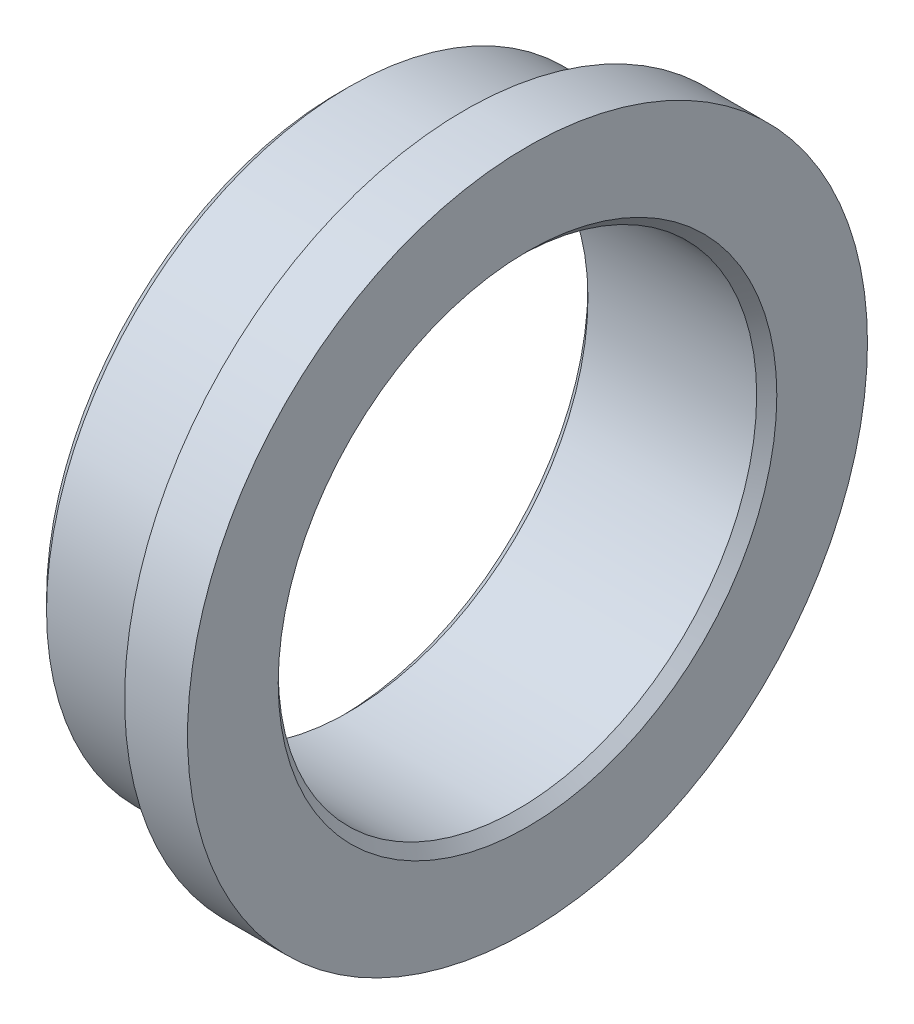
SolidWorks part; units mm, degrees
material "2.1030 (CuSn8P)"
ref_plane "Ebene vorne" through (0, 0, 0) normal (0, 0, 1) x (1, 0, 0)
ref_plane "Ebene oben" through (0, 0, 0) normal (0, 1, 0) x (1, 0, 0)
ref_plane "Ebene rechts" through (0, 0, 0) normal (1, 0, 0) x (0, 0, -1)
ref_axis "A_Drehachse" through (6.5, 0, 0) along (-1, 0, 0)
sketch "Skizze1" plane through (0, 0, 0) normal (0, 0, 1) x (1, 0, 0)
  line L0 (-2, 24) -> (-10, 24)
  line L1 (0, -29.7) -> (0, 29.7) construction
  line L2 (0, 25.3691) -> (0, 27)
  line L3 (0, 27) -> (5, 27)
  line L4 (5, 27) -> (5, 19)
  line L5 (5, 19) -> (-10, 19)
  line L6 (-10, 19) -> (-10, 24)
  line L7 (0, 25.3691) -> (0, 23.8)
  line L8 (0, 23.8) -> (-2, 23.8)
  line L9 (-2, 23.8) -> (-2, 24)
  line L10 (55, 0) -> (-55, 0) construction
  point P14 (-2, 23.9)
  dimension "D1" = 27
  dimension "D2" = 24
  dimension "D3" = 19
  dimension "D4" = 5
  dimension "D5" = 15
  dimension "D6" = 0.2
  dimension "D7" = 2
revolve "Rotation1" add sketch "Skizze1" angle 360 about axis through (6.5, 0, 0) along (-1, 0, 0)
chamfer "Fase1" distance 0.8 angle 45 3 edges at (5, 0, -19) (-10, 0, -24) (-10, 0, -19)
